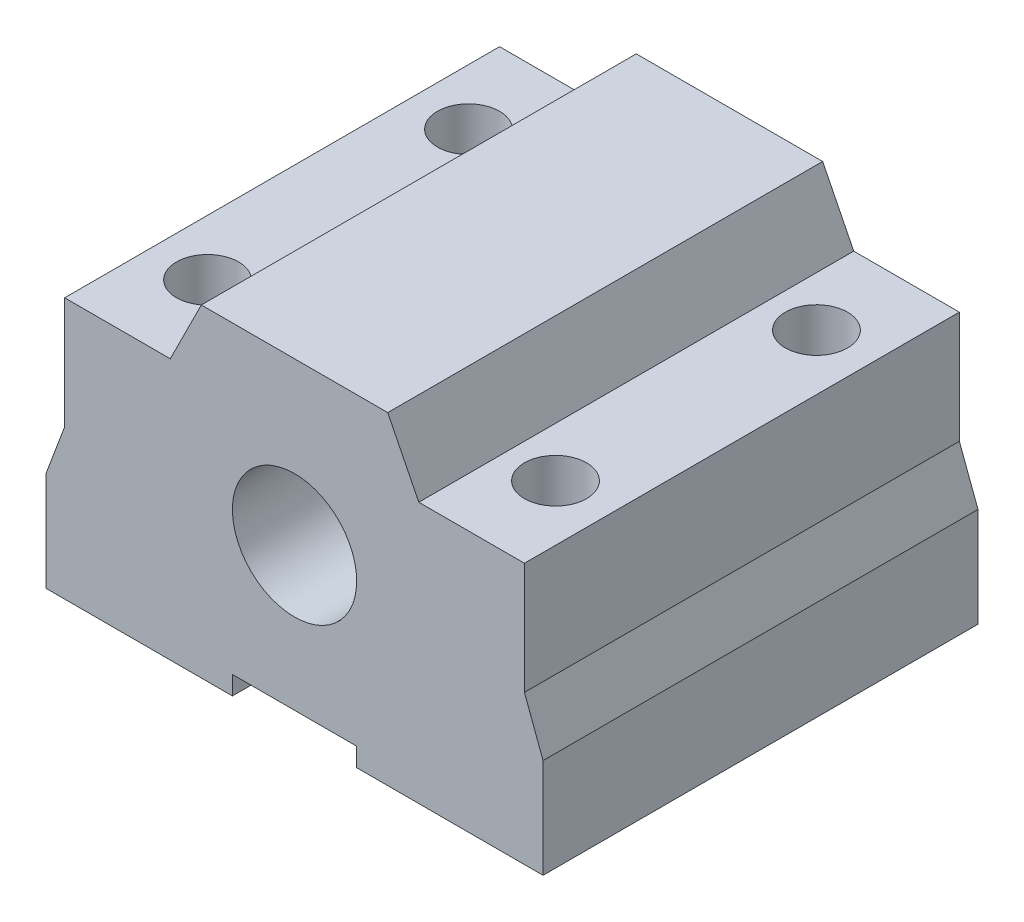
SolidWorks part; units mm, degrees
ref_plane "Спереди" through (0, 0, 0) normal (0, 0, 1) x (1, 0, 0)
ref_plane "Сверху" through (0, 0, 0) normal (0, 1, 0) x (1, 0, 0)
ref_plane "Справа" through (0, 0, 0) normal (1, 0, 0) x (0, 0, -1)
sketch "Эскиз1" plane through (0, 0, 0) normal (0, 0, 1) x (1, 0, 0)
  line L0 (0, 0) -> (0, 21) construction
  line L1 (-18.5, 21) -> (-10, 21)
  line L2 (-18.5, 21) -> (-18.5, 12)
  line L3 (-20, 0) -> (-5, 0)
  line L4 (18.5, 21) -> (18.5, 12)
  line L5 (-7.5, 26) -> (7.5, 26)
  line L6 (18.5, 12) -> (20, 8)
  line L7 (-7.5, 26) -> (-10, 21)
  line L8 (20, 8) -> (20, 0)
  line L9 (10, 21) -> (18.5, 21)
  line L10 (7.5, 26) -> (10, 21)
  line L11 (5, 1.5) -> (5, 0)
  line L12 (-18.5, 12) -> (-20, 8)
  line L13 (-20, 8) -> (-20, 0)
  line L14 (-5, 1.5) -> (5, 1.5)
  line L15 (-5, 1.5) -> (-5, 0)
  line L16 (5, 0) -> (20, 0)
  line L17 (-14, 21) -> (-14, 0) construction
  line L18 (14, 21) -> (14, 0) construction
  circle A0 centre (0, 13) radius 5
  point P24 (0, 21)
  point P26 (0, 0)
  dimension "D12" = 10
  dimension "D1" = 8
  dimension "D2" = 13
  dimension "D3" = 40
  dimension "D4" = 26
  dimension "D5" = 21
  dimension "D6" = 12
  dimension "D7" = 1.5
  dimension "D8" = 1.5
  dimension "D9" = 10
  dimension "D10" = 20
  dimension "D11" = 15
  dimension "D13" = 28
extrude "Бобышка-Вытянуть1" add sketch "Эскиз1" along normal blind 35
sketch "Эскиз2" plane through (0, 0, 0) normal (0, -1, 0) x (1, 0, 0)
  line L0 (-14, 0) -> (-14, 35) construction
  line L1 (-20, 0) -> (-5, 0) construction
  line L2 (-20, 35) -> (-5, 35) construction
  line L3 (14, 0) -> (14, 35) construction
  line L4 (5, 0) -> (20, 0) construction
  line L5 (5, 35) -> (20, 35) construction
  line L6 (0, 0) -> (0, 35) construction
  line L7 (-20, 28) -> (20, 28) construction
  line L8 (-20, 35) -> (-20, 0) construction
  line L9 (20, 35) -> (20, 0) construction
  line L10 (-20, 17.5) -> (20, 17.5) construction
  line L11 (-20, 7) -> (20, 7) construction
  circle A0 centre (-14, 28) radius 2.5
  circle A1 centre (14, 28) radius 2.5
  circle A2 centre (14, 7) radius 2.5
  circle A3 centre (-14, 7) radius 2.5
  dimension "D1" = 5
  dimension "D2" = 28
  dimension "D3" = 21
extrude "Вырез-Вытянуть1" cut sketch "Эскиз2" against normal through all
